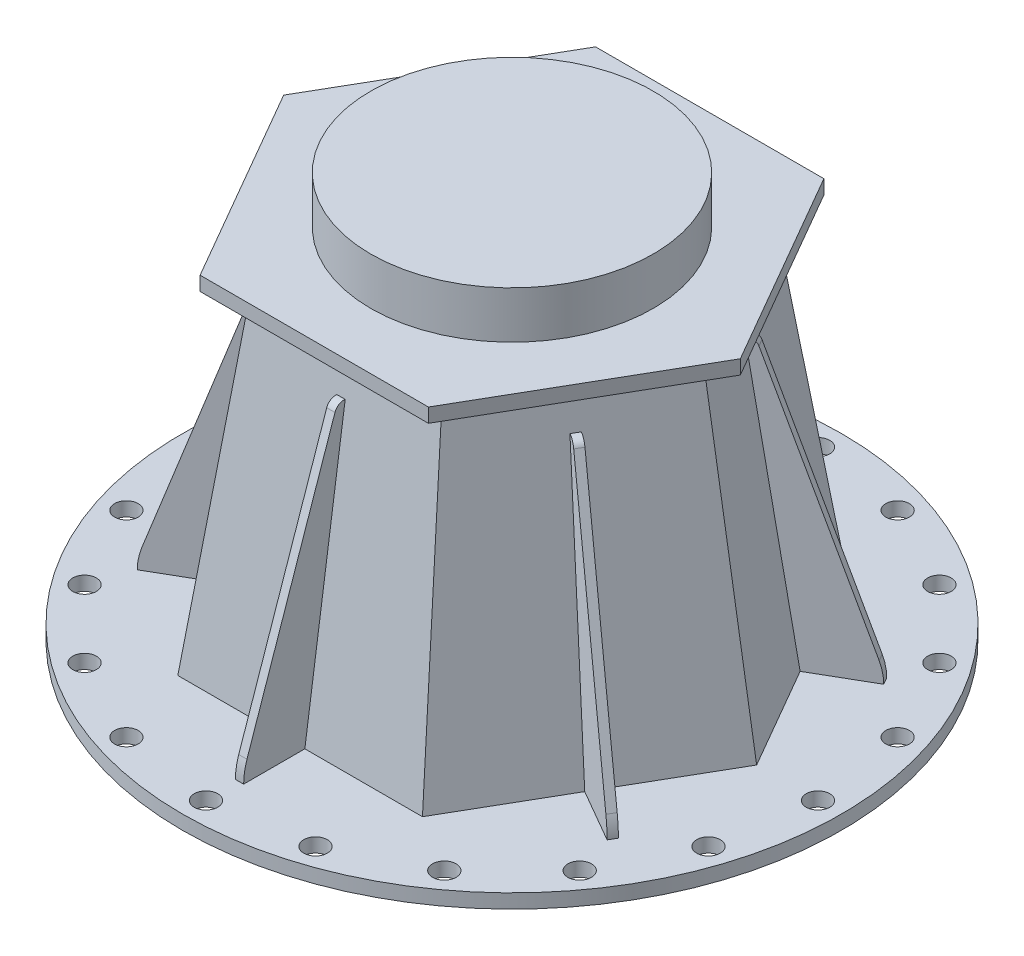
SolidWorks part; units mm, degrees
material "Plain Carbon Steel"
ref_plane "Front Plane" through (0, 0, 0) normal (0, 0, 1) x (1, 0, 0)
ref_plane "Top Plane" through (0, 0, 0) normal (0, 1, 0) x (1, 0, 0)
ref_plane "Right Plane" through (0, 0, 0) normal (1, 0, 0) x (0, 0, -1)
sketch "Sketch1" plane through (0, 0, 0) normal (0, 1, 0) x (1, 0, 0)
  circle A0 centre (0, 0) radius 300
  dimension "D1" = 600
extrude "Boss-Extrude1" add sketch "Sketch1" against normal blind 100
ref_plane "Plane1" through (0, -100, 0) normal (0, -1, 0) x (1, 0, 0)
sketch "Sketch2" plane through (0, -100, 0) normal (0, -1, 0) x (1, 0, 0)
  line L0 (0, 690.6845) -> (0, -321.7339) construction
  line L1 (484.9742, 0) -> (242.4871, 420)
  line L2 (242.4871, 420) -> (-242.4871, 420)
  line L3 (-242.4871, 420) -> (-484.9742, 0)
  line L4 (-484.9742, 0) -> (-242.4871, -420)
  line L5 (-242.4871, -420) -> (242.4871, -420)
  line L6 (242.4871, -420) -> (484.9742, 0)
  circle A0 centre (0, 0) radius 420 construction
  circle A2 centre (0, 0) radius 350 construction
  dimension "D1" = 70
  dimension "D2" = 700
extrude "Boss-Extrude2" add sketch "Sketch2" along normal blind 30 separate body
ref_plane "Plane2" through (0, -130, 0) normal (0, -1, 0) x (-1, 0, 0)
sketch "Sketch5" plane through (0, -130, 0) normal (0, -1, 0) x (-1, 0, 0)
  line L0 (-484.9742, 0) -> (-242.4871, -420) construction
  line L1 (-404.1452, 0) -> (-202.0726, -350)
  line L2 (-202.0726, -350) -> (202.0726, -350)
  line L3 (202.0726, -350) -> (404.1452, 0)
  line L4 (404.1452, 0) -> (202.0726, 350)
  line L5 (202.0726, 350) -> (-202.0726, 350)
  line L6 (-202.0726, 350) -> (-404.1452, 0)
  line L7 (-484.9742, 0) -> (-242.4871, -420) construction
  line L8 (-242.4871, 420) -> (-484.9742, 0) construction
  circle A0 centre (0, 0) radius 350 construction
  circle A2 centre (0, 0) radius 300
  circle A3 centre (0, 0) radius 300 construction
  dimension "D1" = 0
  dimension "D2" = 70
ref_plane "Plane3" through (0, -830, 0) normal (0, -1, 0) x (-1, 0, 0)
sketch "Sketch6" plane through (0, -830, 0) normal (0, -1, 0) x (-1, 0, 0)
  line L7 (-202.0726, -350) -> (202.0726, -350) construction
  line L8 (-519.6152, 0) -> (-259.8076, -450)
  line L9 (-259.8076, -450) -> (259.8076, -450)
  line L10 (259.8076, -450) -> (519.6152, 0)
  line L11 (519.6152, 0) -> (259.8076, 450)
  line L12 (259.8076, 450) -> (-259.8076, 450)
  line L13 (-259.8076, 450) -> (-519.6152, 0)
  line L14 (-202.0726, -350) -> (202.0726, -350) construction
  circle A3 centre (0, 0) radius 350 construction
  circle A4 centre (0, 0) radius 350 construction
  circle A5 centre (0, 0) radius 450 construction
  point P1 (-484.9742, 0)
  dimension "D1" = 100
loft "Loft2" add profiles "Sketch5", "Sketch6"
sketch "Sketch11" plane through (0, -830, 0) normal (0, -1, 0) x (-1, 0, 0)
  circle A0 centre (0, 0) radius 700
  circle A1 centre (0, 0) radius 450 construction
  circle A2 centre (0, 0) radius 450 construction
  dimension "D1" = 250
extrude "Boss-Extrude4" add sketch "Sketch11" along normal blind 30
sketch "Sketch12" plane through (0, -830, 0) normal (0, -1, 0) x (-1, 0, 0)
  line L0 (0, 0) -> (700, 0) construction
  circle A0 centre (0, 0) radius 700 construction
  circle A1 centre (0, 0) radius 700 construction
  circle A2 centre (0, 0) radius 650 construction
  circle A3 centre (650, 0) radius 25
  dimension "D1" = 50
  dimension "D2" = 50
extrude "Cut-Extrude2" cut sketch "Sketch12" along normal through all contours A3
sketch "Sketch13" plane through (0, -830, 0) normal (0, -1, 0) x (-1, 0, 0)
  circle A0 centre (0, 0) radius 650 construction
  circle A1 centre (0, 0) radius 650
pattern_curve "CrvPattern2" of "Cut-Extrude2" parameters "D1"=20, "D3"=10, "D2"=1, "D4"=10
sketch "Sketch15" plane through (0, 0, 0) normal (1, 0, 0) x (0, 0, -1)
  line L3 (407.0604, -830) -> (357.0604, -830) construction
  line L6 (-350, -130) -> (-450, -830) construction
  line L7 (-364.2857, -230) -> (-450, -830)
  line L10 (-580, -830) -> (-450, -830)
  line L11 (-386.0304, -243.3049) -> (-572.956, -787.7882)
  arc A0 (-386.0304, -243.3049) -> (-364.2857, -230) centre (-367.1141, -249.799) cw
  arc A2 (-580, -830) -> (-572.956, -787.7882) centre (-450, -830) cw
  point P15 (-450, -830)
  dimension "D4" = 20
  dimension "D3" = 130
  dimension "D1" = 600
extrude "Boss-Extrude5" add sketch "Sketch15" along normal blind 10 and the other way blind 7.5
pattern_circular "CirPattern1" count 6 over 360 about axis through (0, 0, 0) along (0, 1, 0) of "Boss-Extrude5"
ref_plane "Plane4" through (0, -860, 0) normal (0, -1, 0) x (-1, 0, 0)
ref_point "Point1"
